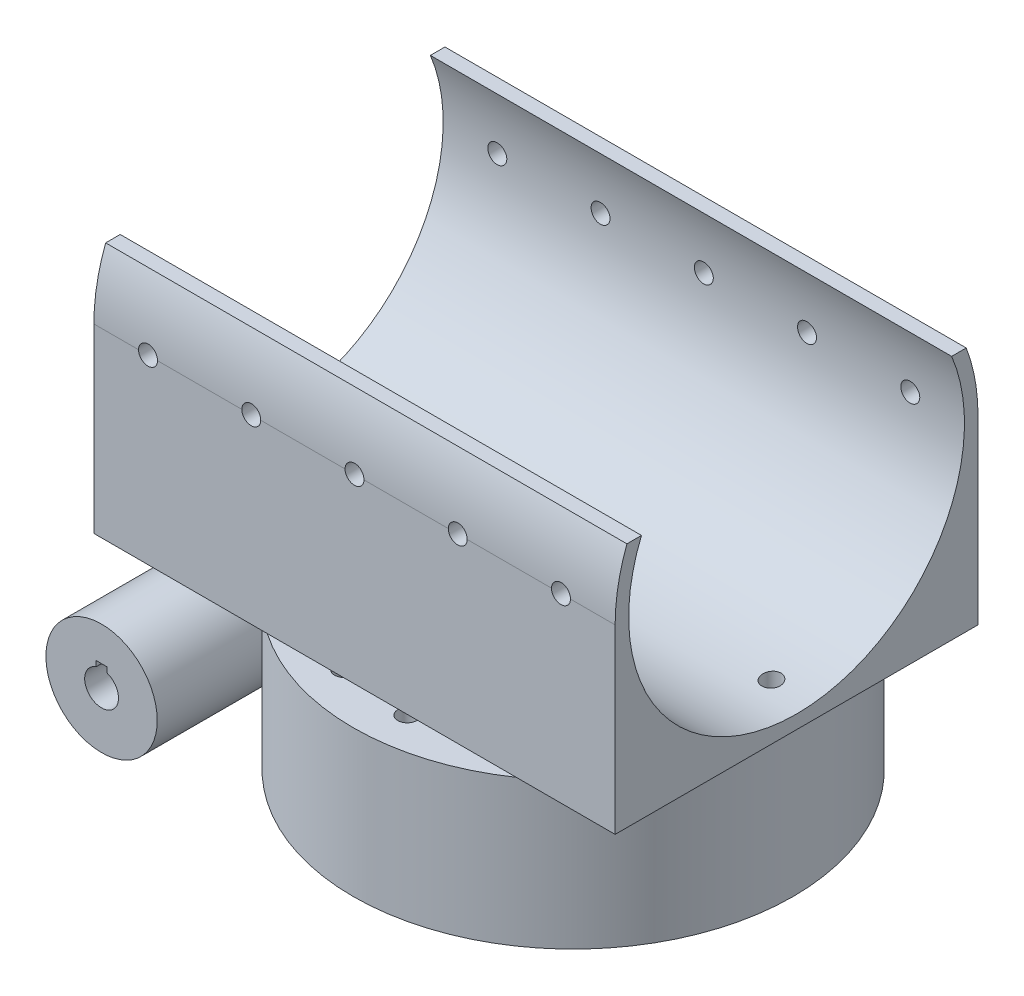
SolidWorks part; units mm, degrees
ref_plane "Front Plane" through (0, 0, 0) normal (0, 0, 1) x (1, 0, 0)
ref_plane "Top Plane" through (0, 0, 0) normal (0, 1, 0) x (1, 0, 0)
ref_plane "Right Plane" through (0, 0, 0) normal (1, 0, 0) x (0, 0, -1)
sketch "Sketch1" plane through (0, 0, 0) normal (0, 1, 0) x (1, 0, 0)
  circle A0 centre (0, 0) radius 162.5
  dimension "D1" = 325
extrude "Boss-Extrude1" add sketch "Sketch1" along normal blind 108
sketch "Sketch2" plane through (0, 108, 0) normal (0, 1, 0) x (1, 0, 0)
  circle A0 centre (0, 0) radius 72.5
  dimension "D1" = 145
extrude "Cut-Extrude1" cut sketch "Sketch2" against normal blind 108
sketch "Sketch3" plane through (0, 108, 0) normal (0, 1, 0) x (1, 0, 0)
  circle A0 centre (0, 0) radius 112
  dimension "D1" = 224
extrude "Cut-Extrude2" cut sketch "Sketch3" against normal blind 29
ref_plane "Plane1" through (0, 0, 174.15) normal (0, 0, 1) x (1, 0, 0)
ref_plane "Plane2" through (-220, 0, 0) normal (1, 0, 0) x (0, 0, -1)
sketch "Sketch5" plane through (0, 108, 0) normal (0, 1, 0) x (1, 0, 0)
  circle A0 centre (0, 0) radius 135 construction
  circle A1 centre (-103.5465, 86.6206) radius 7
  circle A2 centre (-62.5162, 119.6525) radius 7
  circle A3 centre (-11.9684, 134.4684) radius 7
  circle A4 centre (40.4015, 128.8127) radius 7
  circle A5 centre (86.6206, 103.5465) radius 7
  circle A6 centre (119.6525, 62.5162) radius 7
  circle A7 centre (134.4684, 11.9684) radius 7
  circle A8 centre (128.8127, -40.4015) radius 7
  circle A9 centre (103.5465, -86.6206) radius 7
  circle A10 centre (62.5162, -119.6525) radius 7
  circle A11 centre (11.9684, -134.4684) radius 7
  circle A12 centre (-40.4015, -128.8127) radius 7
  circle A13 centre (-86.6206, -103.5465) radius 7
  circle A14 centre (-119.6525, -62.5162) radius 7
  circle A15 centre (-134.4684, -11.9684) radius 7
  circle A16 centre (-128.8127, 40.4015) radius 7
  point P38 (0, 0)
  dimension "D1" = 270
  dimension "D2" = 14
  dimension "D3" = 16
extrude "Cut-Extrude4" cut sketch "Sketch5" against normal through all both and the other way through all
sketch "Sketch6" plane through (0, 0, 174.15) normal (0, 0, 1) x (1, 0, 0)
  line L0 (162.5, 108) -> (-162.5, 108) construction
  circle A0 centre (-174.15, 51.9) radius 41.125
  dimension "D3" = 82.25
  dimension "D1" = 174.15
  dimension "D2" = 56.1
extrude "Boss-Extrude2" add sketch "Sketch6" against normal blind 322
sketch "Sketch14" plane through (-220, 0, 0) normal (1, 0, 0) x (0, 0, -1)
  line L0 (162.5, 108) -> (-162.5, 108) construction
  line L1 (134, 242) -> (134, 108)
  line L2 (-134, 242) -> (-134, 108)
  line L4 (0, 382.2771) -> (0, 0) construction
  line L7 (162.5, 108) -> (-134, 108)
  line L11 (-125.2986, 289.5) -> (125.2986, 289.5)
  arc A0 (-114.5415, 289.5) -> (114.5415, 289.5) centre (0, 242) ccw
  arc A2 (-125.2986, 289.5) -> (-134, 242) centre (0, 242) ccw
  arc A3 (-123.7787, 293.3306) -> (123.7787, 293.3306) centre (0, 242) ccw construction
  arc A4 (134, 242) -> (125.2986, 289.5) centre (0, 242) ccw
  point P1 (0, 118)
  dimension "D1" = 248
  dimension "D2" = 47.5
  dimension "D3" = 10
  dimension "D4" = 10
extrude "Boss-Extrude6" add sketch "Sketch14" along normal blind 385
sketch "Sketch7" plane through (0, 0, 174.15) normal (0, 0, 1) x (1, 0, 0)
  circle A0 centre (-174.15, 51.9) radius 12.5
  dimension "D1" = 25
extrude "Cut-Extrude5" cut sketch "Sketch7" against normal blind 66
sketch "Sketch8" plane through (0, 0, 174.15) normal (0, 0, 1) x (1, 0, 0)
  line L0 (-174.15, 51.9) -> (-174.15, 39.4) construction
  line L1 (-178.15, 51.9) -> (-170.15, 51.9)
  line L2 (-178.15, 51.9) -> (-178.15, 67.7)
  line L3 (-178.15, 67.7) -> (-170.15, 67.7)
  line L4 (-170.15, 51.9) -> (-170.15, 67.7)
  circle A0 centre (-174.15, 51.9) radius 12.5 construction
  circle A1 centre (-174.15, 51.9) radius 12.5
  point P8 (-174.15, 51.9)
  circle M6 centre (-174.15, 51.9) radius 12.5
  dimension "D1" = 28.3
  dimension "D2" = 8
extrude "Cut-Extrude6" cut sketch "Sketch8" against normal blind 66 contours L4 L3 L2 M6
sketch "Sketch15" plane through (0, 0, 0) normal (0, -1, 0) x (1, 0, 0)
  circle A0 centre (-134.4684, 11.9684) radius 7 construction
  circle A1 centre (-134.4684, 11.9684) radius 7
  circle A2 centre (134.4684, -11.9684) radius 7 construction
  circle A3 centre (134.4684, -11.9684) radius 7
extrude "Cut-Extrude7" cut sketch "Sketch15" against normal blind 385
sketch "Sketch16" plane through (0, 0, -134) normal (0, 0, -1) x (-1, 0, 0)
  line L0 (-165, 242) -> (220, 242) construction
  line L3 (220, 159.225) -> (220, -159.225) construction
  line L4 (-165, 242) -> (-165, 108) construction
  circle A0 centre (-125, 242) radius 7
  circle A1 centre (-48.75, 242) radius 7
  circle A2 centre (27.5, 242) radius 7
  circle A3 centre (103.75, 242) radius 7
  circle A4 centre (180, 242) radius 7
  dimension "D1" = 14
  dimension "D2" = 5
  dimension "D3" = 40
  dimension "D4" = 40
extrude "Cut-Extrude8" cut sketch "Sketch16" against normal through all both and the other way through all
equation "\"h\"= 108"
equation "\"ind\"= 145"
equation "\"outd\"=224"
equation "\"D1@Boss-Extrude1\"=\"h\""
equation "\"D1@Sketch3\"=\"outd\""
equation "\"D1@Cut-Extrude2\"=\"h\"-35-44"
equation "\"out_shaft\"= 248"
equation "\"D1@Sketch14\"=\"out_shaft\""
